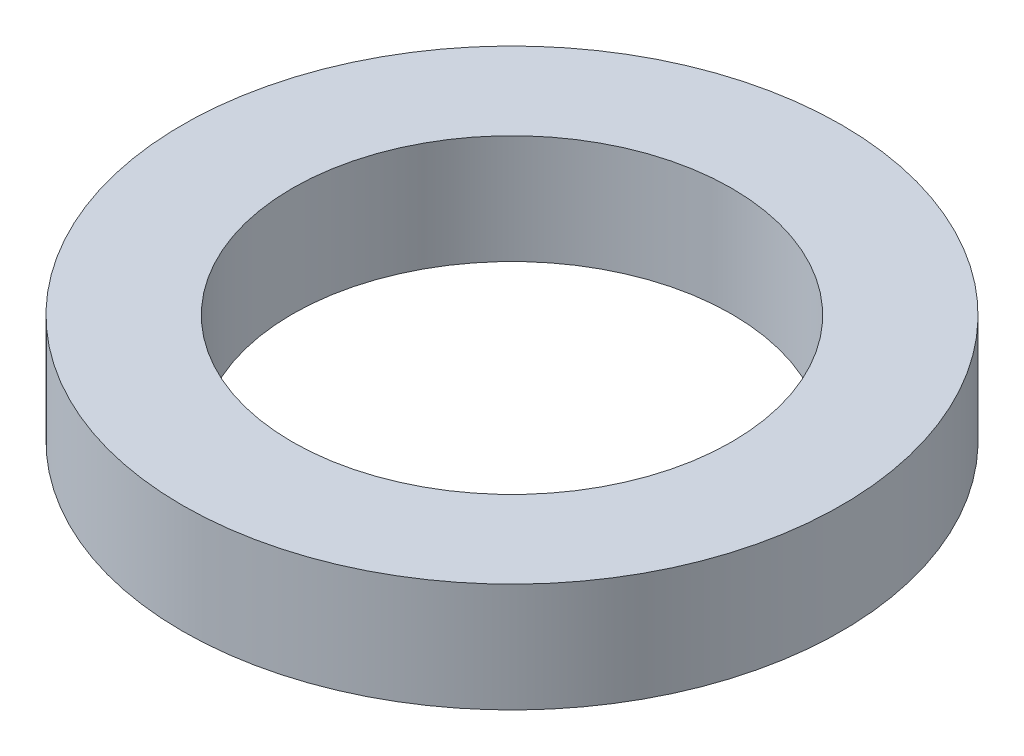
SolidWorks part; units mm, degrees
ref_plane "Front Plane" through (0, 0, 0) normal (0, 0, 1) x (1, 0, 0)
ref_plane "Top Plane" through (0, 0, 0) normal (0, 1, 0) x (1, 0, 0)
ref_plane "Right Plane" through (0, 0, 0) normal (1, 0, 0) x (0, 0, -1)
sketch "Sketch1" plane through (0, 0, 0) normal (0, 1, 0) x (1, 0, 0)
  circle A0 centre (0, 0) radius 3.175
  circle A1 centre (0, 0) radius 4.7625
  dimension "D1" = 6.35
  dimension "D2" = 9.525
extrude "Boss-Extrude1" add sketch "Sketch1" along normal blind 1.5748
